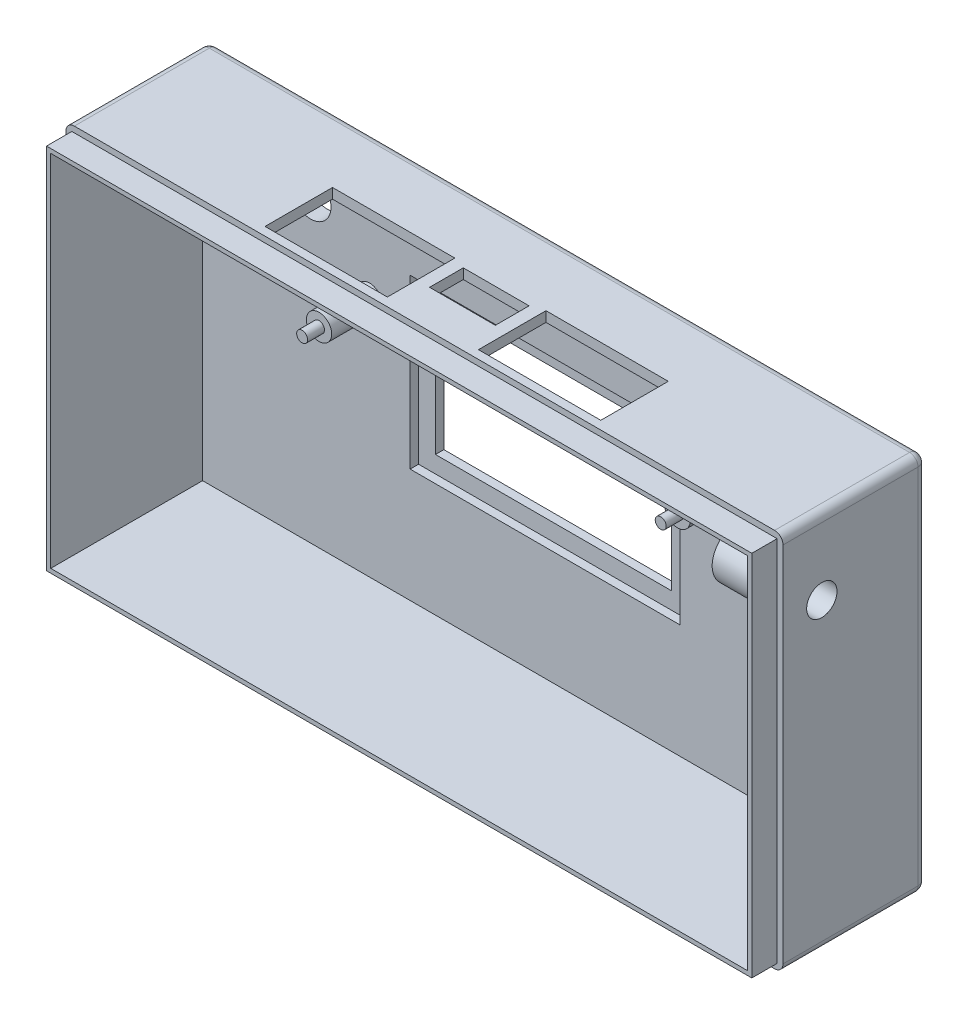
SolidWorks part; units mm, degrees
material "ABS"
ref_plane "Спереди" through (0, 0, 0) normal (0, 0, 1) x (1, 0, 0)
ref_plane "Сверху" through (0, 0, 0) normal (0, 1, 0) x (1, 0, 0)
ref_plane "Справа" through (0, 0, 0) normal (1, 0, 0) x (0, 0, -1)
sketch "Эскиз1" plane through (0, 0, 0) normal (0, 0, 1) x (1, 0, 0)
  line L1 (0, 0) -> (85, 0)
  line L2 (0, 0) -> (0, 45)
  line L3 (0, 45) -> (85, 45)
  line L4 (85, 0) -> (85, 45)
  dimension "D1" = 85
  dimension "D2" = 45
extrude "Бобышка-Вытянуть1" add sketch "Эскиз1" along normal blind 20
sketch "Эскиз2" plane through (0, 0, 20) normal (0, 0, 1) x (1, 0, 0)
  line L0 (42.5, 45) -> (42.5, 0) construction
  line L1 (85, 45) -> (0, 45) construction
  line L2 (0, 0) -> (85, 0) construction
  line L3 (85, 0) -> (85, 45) construction
  line L4 (1.2, 43.8) -> (83.8, 43.8)
  line L5 (1.2, 43.8) -> (1.2, 1.2)
  line L6 (1.2, 1.2) -> (83.8, 1.2)
  line L7 (83.8, 43.8) -> (83.8, 1.2)
  line L8 (1.2, 43.8) -> (83.8, 1.2) construction
  line L9 (1.2, 1.2) -> (83.8, 43.8) construction
  point P6 (42.5, 22.5)
  dimension "D1" = 1.2
  dimension "D2" = 1.2
extrude "Вырез-Вытянуть1" cut sketch "Эскиз2" against normal blind 18
sketch "Эскиз3" plane through (0, 0, 20) normal (0, 0, 1) x (1, 0, 0)
  line L0 (42.5, 45) -> (42.5, 0) construction
  line L1 (85, 45) -> (0, 45) construction
  line L2 (0, 0) -> (85, 0) construction
  line L3 (0, 45) -> (0, 0) construction
  line L4 (0.7, 44.3) -> (84.3, 44.3)
  line L5 (0.7, 44.3) -> (0.7, 0.7)
  line L6 (0.7, 0.7) -> (84.3, 0.7)
  line L7 (84.3, 44.3) -> (84.3, 0.7)
  line L8 (0.7, 44.3) -> (84.3, 0.7) construction
  line L9 (0.7, 0.7) -> (84.3, 44.3) construction
  circle A0 centre (42.5, 22.5) radius 52.5648
  point P6 (42.5, 22.5)
  dimension "D1" = 0.7
  dimension "D2" = 0.7
extrude "Вырез-Вытянуть2" cut sketch "Эскиз3" against normal blind 3
sketch "Эскиз4" plane through (85, 0, 0) normal (-1, 0, 0) x (0, 0, 1)
  line L0 (17, 45) -> (0, 45) construction
  line L1 (0, 45) -> (0, 0) construction
  circle A0 centre (12.4, 36.05) radius 1.5
  dimension "D1" = 8.95
  dimension "D2" = 3
  dimension "D3" = 12.4
extrude "Вырез-Вытянуть3" cut sketch "Эскиз4" along normal blind 10
sketch "Эскиз6" plane through (0, 0, 2) normal (0, 0, 1) x (1, 0, 0)
  line L0 (63.5, 32) -> (21, 32) construction
  line L2 (21, 32) -> (21, 29.89) construction
  circle A0 centre (21, 29.89) radius 1.5
  circle A1 centre (63.5, 32) radius 1.5
  dimension "D2" = 3
  dimension "D3" = 3
  dimension "D5" = 21
  dimension "D1" = 42.5
  dimension "D4" = 2.11
  dimension "D6" = 32
extrude "Бобышка-Вытянуть2" add sketch "Эскиз6" along normal blind 6
sketch "Эскиз7" plane through (0, 0, 8) normal (0, 0, 1) x (1, 0, 0)
  circle A0 centre (21, 29.89) radius 0.65
  circle A1 centre (63.5, 32) radius 0.65
  dimension "D1" = 1.3
  dimension "D2" = 1.3
extrude "Бобышка-Вытянуть3" add sketch "Эскиз7" along normal blind 2
sketch "Эскиз5" plane through (0, 0, 0) normal (0, 0, -1) x (-1, 0, 0)
  line L1 (-55.8, 32.59) -> (-27.8, 32.59)
  line L2 (-55.8, 32.59) -> (-55.8, 16.69)
  line L3 (-55.8, 16.69) -> (-27.8, 16.69)
  line L4 (-27.8, 32.59) -> (-27.8, 16.69)
  circle A0 centre (-21, 29.89) radius 1.5 construction
  dimension "D3" = 6.8
  dimension "D4" = 2.7
  dimension "D1" = 28
  dimension "D2" = 15.9
extrude "Вырез-Вытянуть4" cut sketch "Эскиз5" against normal through all
sketch "Эскиз9" plane through (0, 0, 2) normal (0, 0, 1) x (1, 0, 0)
  line L0 (27.8, 32.59) -> (55.8, 16.69) construction
  line L1 (55.8, 32.59) -> (27.8, 16.69) construction
  line L2 (55.8, 32.59) -> (27.8, 32.59) construction
  line L3 (25.8, 14.69) -> (57.8, 14.69)
  line L4 (25.8, 14.69) -> (25.8, 34.59)
  line L5 (25.8, 34.59) -> (57.8, 34.59)
  line L6 (57.8, 14.69) -> (57.8, 34.59)
  line L7 (25.8, 14.69) -> (57.8, 34.59) construction
  line L8 (25.8, 34.59) -> (57.8, 14.69) construction
  line L9 (55.8, 16.69) -> (55.8, 32.59) construction
  point P8 (41.8, 24.64)
  dimension "D1" = 2
  dimension "D2" = 2
extrude "Вырез-Вытянуть5" cut sketch "Эскиз9" against normal blind 1
sketch "Эскиз10" plane through (0, 45, 0) normal (0, -1, 0) x (1, 0, 0)
  line L0 (37.1, 8) -> (47.9, 8) construction
  line L1 (22.6, 8) -> (37.1, 8)
  line L2 (22.6, 8) -> (22.6, 16)
  line L3 (22.6, 16) -> (37.1, 16)
  line L4 (37.1, 8) -> (37.1, 16)
  line L5 (47.9, 8) -> (62.4, 8)
  line L6 (47.9, 8) -> (47.9, 16)
  line L7 (47.9, 16) -> (62.4, 16)
  line L8 (62.4, 8) -> (62.4, 16)
  line L9 (37.1, 16) -> (47.9, 16) construction
  line L10 (42.5, 8.5) -> (42.5, 8) construction
  line L11 (38.6, 12.5) -> (46.4, 12.5)
  line L12 (38.6, 12.5) -> (38.6, 8.5)
  line L13 (38.6, 8.5) -> (46.4, 8.5)
  line L14 (46.4, 12.5) -> (46.4, 8.5)
  line L15 (0, 17) -> (0, 0) construction
  line L16 (0, 0) -> (85, 0) construction
  dimension "D1" = 14.5
  dimension "D2" = 14.5
  dimension "D3" = 8
  dimension "D4" = 7.8
  dimension "D5" = 4
  dimension "D6" = 10.8
  dimension "D7" = 1
  dimension "D8" = 42.5
  dimension "D9" = 8
extrude "Вырез-Вытянуть6" cut sketch "Эскиз10" along normal blind 10
fillet "Скругление1" radius 1 8 edges at (0, 22.5, 0) (85, 22.5, 0) (42.5, 0, 0) (42.5, 45, 0) (0, 0, 8.5) (0, 45, 8.5) (85, 45, 8.5) (85, 0, 8.5)
sketch "Эскиз11" plane through (85, 0, 0) normal (-1, 0, 0) x (0, 0, 1)
  line L0 (0, 36.05) -> (12.4, 36.05) construction
  line L1 (0, 1) -> (0, 44) construction
  line L2 (1, 34.3) -> (1, 37.8)
  line L3 (1, 44) -> (1, 1) construction
  line L4 (1, 37.8) -> (10.7417, 38.55)
  line L5 (1, 34.3) -> (10.7417, 33.55)
  line L6 (0, 44) -> (0, 1) construction
  circle A0 centre (12.4, 36.05) radius 1.8
  circle A1 centre (12.4, 36.05) radius 3
  point P15 (1, 36.05)
  line M14 (1, 1) -> (1, 44)
  dimension "D1" = 6
  dimension "D2" = 3.6
  dimension "D3" = 3.5
  dimension "D4" = 5
extrude "Бобышка-Вытянуть4" add sketch "Эскиз11" along normal blind 10 contours L0 L2 L5 A1 | L0 L2 L4 A1 | L0 A1 L5 M14
sketch "Эскиз12" plane through (75, 0, 0) normal (-1, 0, 0) x (0, 0, 1)
  circle A0 centre (12.4, 36.05) radius 1.8
  dimension "D1" = 3.6
extrude "Вырез-Вытянуть7" cut sketch "Эскиз12" against normal through all
sketch "Эскиз13" plane through (0, 0, 2) normal (0, 0, 1) x (1, 0, 0)
  circle A0 centre (14, 36.89) radius 2.425
  circle A1 centre (21, 29.89) radius 0.65 construction
  circle A2 centre (21, 29.89) radius 0.65 construction
  dimension "D1" = 4.85
  dimension "D2" = 7
  dimension "D3" = 7
extrude "Вырез-Вытянуть8" cut sketch "Эскиз13" against normal through all
